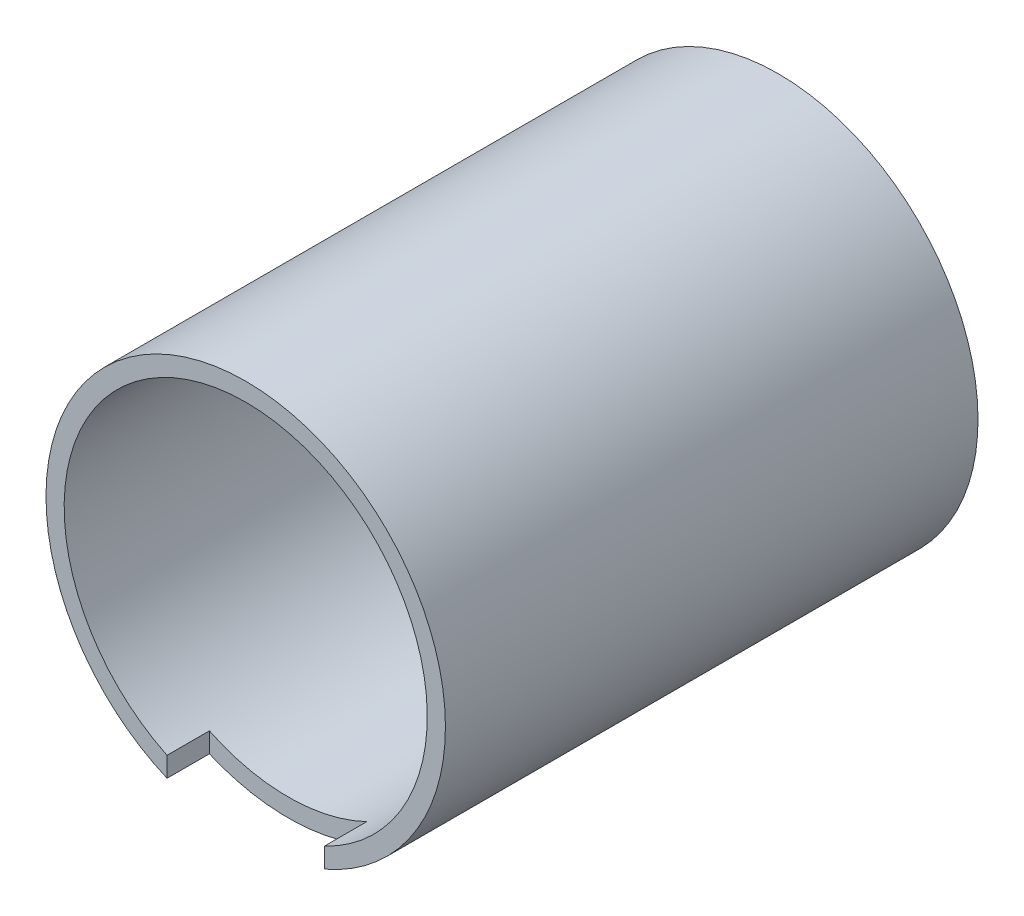
SolidWorks part; units mm, degrees
ref_plane "Front Plane" through (0, 0, 0) normal (0, 0, 1) x (1, 0, 0)
ref_plane "Top Plane" through (0, 0, 0) normal (0, 1, 0) x (1, 0, 0)
ref_plane "Right Plane" through (0, 0, 0) normal (1, 0, 0) x (0, 0, -1)
sketch "Sketch1" plane through (0, 0, 0) normal (0, 0, 1) x (1, 0, 0)
  circle A0 centre (0, 0) radius 16.5
  circle A1 centre (0, 0) radius 15
  dimension "D1" = 33
  dimension "D2" = 30
extrude "Boss-Extrude1" add sketch "Sketch1" along normal blind 44
sketch "Sketch2" plane through (0, 0, 0) normal (0, 1, 0) x (1, 0, 0)
  line L0 (-6.5, 0) -> (6.5, 0)
  line L1 (16.5, 0) -> (-16.5, 0) construction
  line L2 (6.5, 0) -> (6.5, -3.5)
  line L3 (6.5, -3.5) -> (-6.5, -3.5)
  line L4 (-6.5, -3.5) -> (-6.5, 0)
  line L5 (-16.5, -22) -> (-24.6225, -22) construction
  line L6 (-16.5, 0) -> (-16.5, -44) construction
  line L7 (-6.5, -40.5) -> (-6.5, -44)
  line L8 (6.5, -40.5) -> (-6.5, -40.5)
  line L9 (6.5, -44) -> (6.5, -40.5)
  line L10 (-6.5, -44) -> (6.5, -44)
  point P6 (0, 0)
  point P17 (0, -44)
  dimension "D1" = 13
  dimension "D2" = 3.5
extrude "Cut-Extrude1" cut sketch "Sketch2" against normal blind 44
